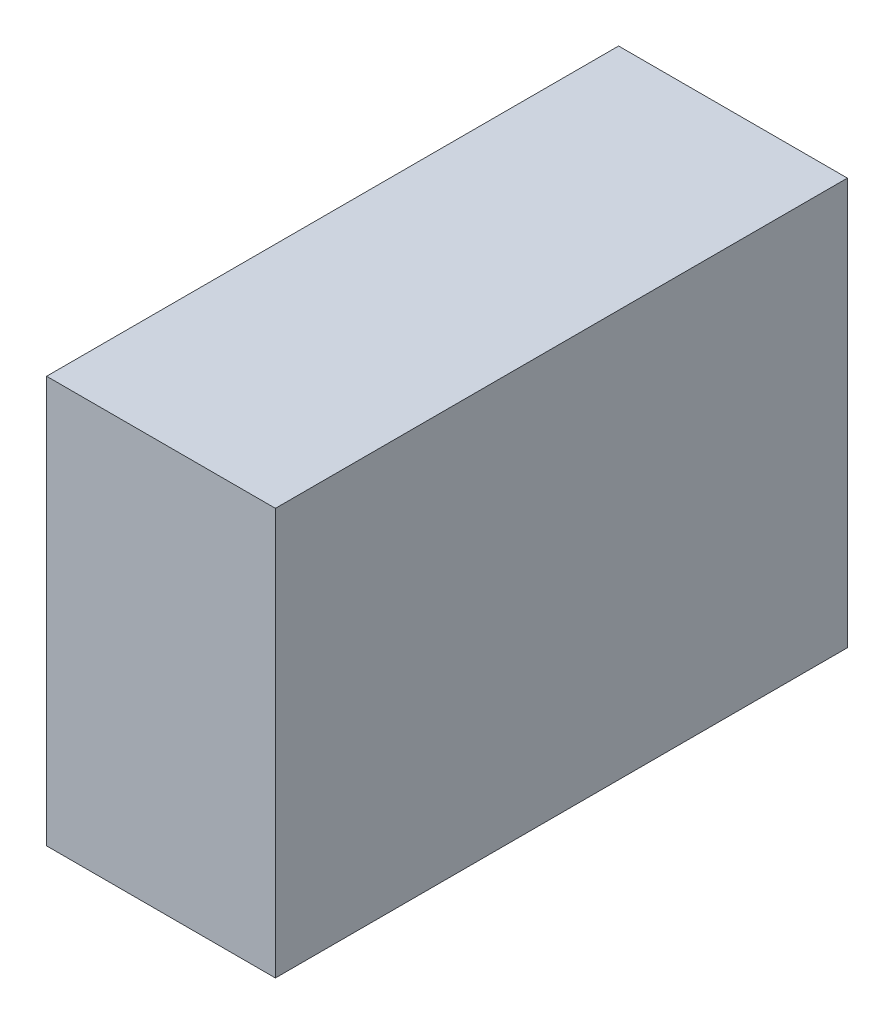
SolidWorks part; units mm, degrees
ref_plane "Front" through (0, 0, 0) normal (0, 0, 1) x (1, 0, 0)
ref_plane "Top" through (0, 0, 0) normal (0, 1, 0) x (1, 0, 0)
ref_plane "Right" through (0, 0, 0) normal (1, 0, 0) x (0, 0, -1)
sketch "Sketch1" plane through (0, 0, 0) normal (0, 1, 0) x (1, 0, 0)
  line L1 (-14.2875, 35.7188) -> (14.2875, 35.7188)
  line L2 (-14.2875, 35.7188) -> (-14.2875, -35.7187)
  line L3 (-14.2875, -35.7187) -> (14.2875, -35.7187)
  line L4 (14.2875, 35.7188) -> (14.2875, -35.7187)
  line L5 (-14.2875, 35.7188) -> (14.2875, -35.7187) construction
  line L6 (-14.2875, -35.7187) -> (14.2875, 35.7188) construction
  point P0 (0, 0)
  dimension "D1" = 28.575
  dimension "D2" = 71.4375
extrude "Boss-Extrude1" add sketch "Sketch1" along normal blind 50.8
